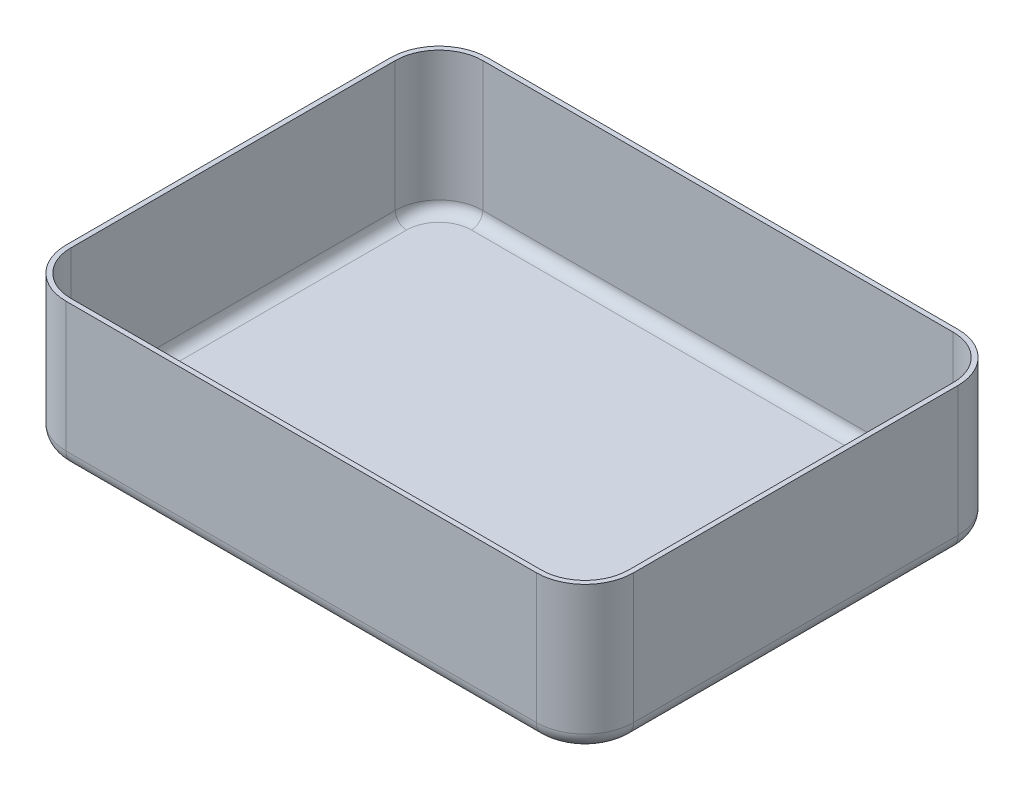
SolidWorks part; units mm, degrees
ref_plane "前基準面" through (0, 0, 0) normal (0, 0, 1) x (1, 0, 0)
ref_plane "上基準面" through (0, 0, 0) normal (0, 1, 0) x (1, 0, 0)
ref_plane "右基準面" through (0, 0, 0) normal (1, 0, 0) x (0, 0, -1)
sketch "草圖1" plane through (0, 0, 0) normal (0, 1, 0) x (1, 0, 0)
  line L1 (-175, -130) -> (175, -130)
  line L2 (-175, -130) -> (-175, 130)
  line L3 (-175, 130) -> (175, 130)
  line L4 (175, -130) -> (175, 130)
  line L5 (-175, -130) -> (175, 130) construction
  line L6 (-175, 130) -> (175, -130) construction
  point P0 (0, 0)
  dimension "D1" = 260
  dimension "D2" = 350
extrude "填料-伸長1" add sketch "草圖1" along normal blind 90
fillet "圓角1" radius 30 4 edges at (-175, 45, -130) (-175, 45, 130) (175, 45, -130) (175, 45, 130)
fillet "圓角2" radius 10 8 edges at (-166.2132, 0, 121.2132) (-175, 0, 0) (-166.2132, 0, -121.2132) (0, 0, -130) (166.2132, 0, -121.2132) (175, 0, 0) (166.2132, 0, 121.2132) (0, 0, 130)
shell "薄殼1" thickness 3
